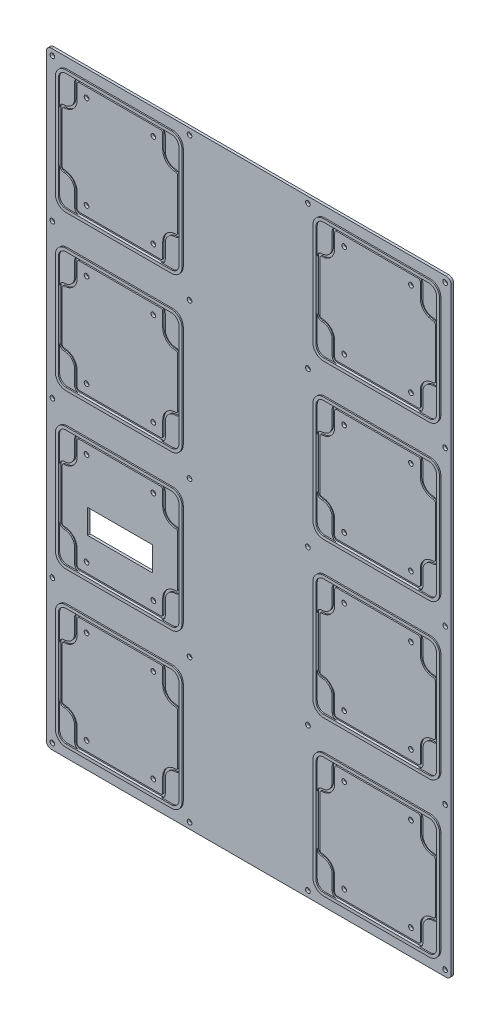
SolidWorks part; units mm, degrees
ref_plane "Front Plane" through (0, 0, 0) normal (0, 0, 1) x (1, 0, 0)
ref_plane "Top Plane" through (0, 0, 0) normal (0, 1, 0) x (1, 0, 0)
ref_plane "Right Plane" through (0, 0, 0) normal (1, 0, 0) x (0, 0, -1)
sketch "Sketch1" plane through (0, 0, 0) normal (0, 0, 1) x (1, 0, 0)
  line L1 (0, 0) -> (254, 0)
  line L2 (0, 0) -> (0, 381)
  line L3 (0, 381) -> (254, 381)
  line L4 (254, 0) -> (254, 381)
  dimension "D1" = 381
  dimension "D2" = 254
extrude "Boss-Extrude1" add sketch "Sketch1" along normal blind 1.5875
sketch "Sketch2" plane through (0, 0, 1.5875) normal (0, 0, 1) x (1, 0, 0)
  line L0 (89.8652, 377.19) -> (89.8652, 3.81) construction
  line L1 (0, 381) -> (254, 381) construction
  line L2 (127, 381) -> (127, 377.19) construction
  line L3 (3.81, 377.19) -> (250.19, 377.19) construction
  line L5 (164.1348, 377.19) -> (164.1348, 3.81) construction
  line L6 (3.81, 377.19) -> (3.81, 3.81) construction
  line L7 (3.81, 3.81) -> (250.19, 3.81) construction
  line L8 (250.19, 3.81) -> (250.19, 377.19) construction
  line L9 (3.81, 190.5) -> (250.19, 190.5) construction
  line L10 (3.81, 287.3756) -> (250.19, 287.3756) construction
  line L11 (3.81, 93.6244) -> (250.19, 93.6244) construction
  line L12 (0, 381) -> (0, 0) construction
  line L13 (0, 190.5) -> (3.81, 190.5) construction
  circle A0 centre (3.81, 377.19) radius 1.4732
  circle A1 centre (89.8652, 377.19) radius 1.4732
  circle A2 centre (164.1348, 377.19) radius 1.4732
  circle A3 centre (250.19, 377.19) radius 1.4732
  circle A4 centre (164.1348, 287.3755) radius 1.4732
  circle A5 centre (3.81, 287.3756) radius 1.4732
  circle A6 centre (250.19, 287.3756) radius 1.4732
  circle A7 centre (89.8652, 287.3756) radius 1.4732
  circle A8 centre (164.1348, 190.5) radius 1.4732
  circle A9 centre (3.81, 191.135) radius 1.4732
  circle A10 centre (250.19, 190.5) radius 1.4732
  circle A11 centre (89.8652, 190.5) radius 1.4732
  circle A12 centre (164.1348, 93.6244) radius 1.4732
  circle A13 centre (3.81, 93.6244) radius 1.4732
  circle A14 centre (250.19, 93.6244) radius 1.4732
  circle A15 centre (89.8652, 93.6244) radius 1.4732
  circle A16 centre (164.1348, 3.81) radius 1.4732
  circle A17 centre (3.81, 3.81) radius 1.4732
  circle A18 centre (250.19, 3.81) radius 1.4732
  circle A19 centre (89.8652, 3.81) radius 1.4732
  dimension "D6" = 2.9464
  dimension "D23" = 0
  dimension "D24" = 0
  dimension "D25" = 0
  dimension "D28" = 0
  dimension "D29" = 0
  dimension "D30" = 0
  dimension "D31" = 0
  dimension "D32" = 86.0552
  dimension "D1" = 246.38
  dimension "D3" = 373.38
  dimension "D4" = 96.8756
  dimension "D5" = 96.8756
  dimension "D7" = 86.0552
  dimension "D8" = 86.0552
  dimension "D9" = 0
  dimension "D10" = 0
  dimension "D11" = 0
  dimension "D12" = 86.0552
  dimension "D13" = 0
  dimension "D14" = 0
  dimension "D15" = 0
  dimension "D16" = 0
  dimension "D17" = 0
  dimension "D18" = 0
  dimension "D19" = 0
  dimension "D20" = 0
  dimension "D21" = 0
  dimension "D22" = 0
  dimension "D26" = 0
  dimension "D27" = 0
extrude "Cut-Extrude1" cut sketch "Sketch2" against normal through all contours A0 | A2 | A3
fillet "Fillet1" radius 3.175 4 edges at (254, 0, 0.7937) (0, 0, 0.7937) (254, 381, 0.7937) (0, 381, 0.7937)
sketch "Sketch3" plane through (0, 0, 1.5875) normal (0, 0, 1) x (1, 0, 0)
  line L0 (9.9695, 45.1866) -> (46.2026, 45.1866) construction
  line L1 (46.2026, 45.1866) -> (46.2026, 9.9695) construction
  line L2 (81.2038, 28.3591) -> (82.4357, 28.3591) construction
  line L3 (82.4357, 29.591) -> (82.4357, 60.7822)
  line L4 (73.0377, 11.2014) -> (73.0377, 20.193)
  line L5 (81.2038, 62.0141) -> (82.4357, 62.0141) construction
  line L6 (71.8058, 9.9695) -> (20.5994, 9.9695)
  line L7 (19.3675, 11.2014) -> (19.3675, 20.193)
  line L8 (11.2014, 28.3591) -> (9.9695, 28.3591) construction
  line L9 (9.9695, 29.591) -> (9.9695, 60.7822)
  line L10 (73.0377, 79.1718) -> (73.0377, 70.1802)
  line L11 (71.8058, 80.4037) -> (20.5994, 80.4037)
  line L12 (3.175, 0) -> (250.825, 0) construction
  line L13 (0, 377.825) -> (0, 3.175) construction
  line L14 (11.2014, 62.0141) -> (9.9695, 62.0141) construction
  line L15 (19.3675, 79.1718) -> (19.3675, 70.1802)
  line L16 (17.78, 79.1718) -> (17.78, 70.1802)
  line L17 (8.382, 29.591) -> (8.382, 60.7822)
  line L18 (17.78, 11.2014) -> (17.78, 20.193)
  line L19 (71.8058, 8.382) -> (20.5994, 8.382)
  line L20 (74.6252, 11.2014) -> (74.6252, 20.193)
  line L21 (84.0232, 29.591) -> (84.0232, 60.7822)
  line L22 (74.6252, 79.1718) -> (74.6252, 70.1802)
  line L23 (71.8058, 81.9912) -> (20.5994, 81.9912)
  arc A0 (19.3675, 20.193) -> (11.2014, 28.3591) centre (11.2014, 20.193) ccw
  arc A1 (9.9695, 29.591) -> (11.2014, 28.3591) centre (11.2014, 29.591) ccw
  arc A2 (19.3675, 11.2014) -> (20.5994, 9.9695) centre (20.5994, 11.2014) ccw
  arc A3 (73.0377, 11.2014) -> (71.8058, 9.9695) centre (71.8058, 11.2014) cw
  arc A4 (82.4357, 29.591) -> (81.2038, 28.3591) centre (81.2038, 29.591) cw
  arc A5 (73.0377, 20.193) -> (81.2038, 28.3591) centre (81.2038, 20.193) cw
  arc A6 (73.0377, 70.1802) -> (81.2038, 62.0141) centre (81.2038, 70.1802) ccw
  arc A7 (82.4357, 60.7822) -> (81.2038, 62.0141) centre (81.2038, 60.7822) ccw
  arc A8 (73.0377, 79.1718) -> (71.8058, 80.4037) centre (71.8058, 79.1718) ccw
  arc A9 (19.3675, 79.1718) -> (20.5994, 80.4037) centre (20.5994, 79.1718) cw
  arc A10 (9.9695, 60.7822) -> (11.2014, 62.0141) centre (11.2014, 60.7822) cw
  arc A11 (19.3675, 70.1802) -> (11.2014, 62.0141) centre (11.2014, 70.1802) cw
  arc A12 (17.78, 70.1802) -> (11.2014, 63.6016) centre (11.2014, 70.1802) cw
  arc A13 (8.382, 60.7822) -> (11.2014, 63.6016) centre (11.2014, 60.7822) cw
  arc A14 (8.382, 29.591) -> (11.2014, 26.7716) centre (11.2014, 29.591) ccw
  arc A15 (17.78, 20.193) -> (11.2014, 26.7716) centre (11.2014, 20.193) ccw
  arc A16 (17.78, 11.2014) -> (20.5994, 8.382) centre (20.5994, 11.2014) ccw
  arc A17 (74.6252, 11.2014) -> (71.8058, 8.382) centre (71.8058, 11.2014) cw
  arc A18 (74.6252, 20.193) -> (81.2038, 26.7716) centre (81.2038, 20.193) cw
  arc A19 (84.0232, 29.591) -> (81.2038, 26.7716) centre (81.2038, 29.591) cw
  arc A20 (84.0232, 60.7822) -> (81.2038, 63.6016) centre (81.2038, 60.7822) ccw
  arc A21 (74.6252, 70.1802) -> (81.2038, 63.6016) centre (81.2038, 70.1802) ccw
  arc A22 (74.6252, 79.1718) -> (71.8058, 81.9912) centre (71.8058, 79.1718) ccw
  arc A23 (17.78, 79.1718) -> (20.5994, 81.9912) centre (20.5994, 79.1718) cw
  point P35 (82.4357, 45.1866)
  dimension "D6" = 8.1661
  dimension "D7" = 2.4638
  dimension "D8" = 1.2319
  dimension "D1" = 9.9695
  dimension "D2" = 9.9695
  dimension "D3" = 19.3675
  dimension "D4" = 28.3591
  dimension "D5" = 45.1866
  dimension "D10" = 46.2026
  dimension "D9" = 1.5875
extrude "Cut-Extrude2" cut sketch "Sketch3" against normal blind 0.7937
sketch "Sketch4" plane through (0, 0, 1.5875) normal (0, 0, 1) x (1, 0, 0)
  line L0 (8.382, 60.7822) -> (8.382, 77.2287)
  line L1 (13.1445, 81.9912) -> (20.5994, 81.9912)
  line L2 (20.5994, 81.9912) -> (79.2607, 81.9912)
  line L3 (84.0232, 77.2287) -> (84.0232, 13.1445)
  line L4 (79.2607, 8.382) -> (13.1445, 8.382)
  line L5 (8.382, 13.1445) -> (8.382, 60.7822)
  line L6 (6.477, 60.7822) -> (6.477, 77.2287)
  line L7 (13.1445, 83.8962) -> (20.5994, 83.8962)
  line L8 (20.5994, 83.8962) -> (79.2607, 83.8962)
  line L9 (85.9282, 77.2287) -> (85.9282, 13.1445)
  line L10 (79.2607, 6.477) -> (13.1445, 6.477)
  line L11 (6.477, 13.1445) -> (6.477, 60.7822)
  arc A0 (13.1445, 81.9912) -> (8.382, 77.2287) centre (13.1445, 77.2287) ccw
  arc A1 (79.2607, 81.9912) -> (84.0232, 77.2287) centre (79.2607, 77.2287) cw
  arc A2 (84.0232, 13.1445) -> (79.2607, 8.382) centre (79.2607, 13.1445) cw
  arc A3 (8.382, 13.1445) -> (13.1445, 8.382) centre (13.1445, 13.1445) ccw
  arc A4 (13.1445, 83.8962) -> (6.477, 77.2287) centre (13.1445, 77.2287) ccw
  arc A5 (79.2607, 83.8962) -> (85.9282, 77.2287) centre (79.2607, 77.2287) cw
  arc A6 (85.9282, 13.1445) -> (79.2607, 6.477) centre (79.2607, 13.1445) cw
  arc A7 (6.477, 13.1445) -> (13.1445, 6.477) centre (13.1445, 13.1445) ccw
  dimension "D1" = 4.7625
  dimension "D2" = 1.905
extrude "Boss-Extrude2" add sketch "Sketch4" along normal blind 0.7937
sketch "Sketch5" plane through (0, 0, 1.5875) normal (0, 0, 1) x (1, 0, 0)
  line L0 (9.9695, 45.1866) -> (82.4357, 45.1866) construction
  line L1 (9.9695, 60.7822) -> (9.9695, 29.591) construction
  line L2 (82.4357, 29.591) -> (82.4357, 60.7822) construction
  line L3 (82.4357, 45.1866) -> (46.2026, 45.1866) construction
  line L4 (46.2026, 45.1866) -> (46.2026, 80.4037) construction
  line L5 (71.8058, 80.4037) -> (20.5994, 80.4037) construction
  circle A0 centre (25.2476, 74.3966) radius 1.4732
  circle A1 centre (67.1576, 74.3966) radius 1.4732
  circle A2 centre (67.1576, 15.9766) radius 1.4732
  circle A3 centre (25.2476, 15.9766) radius 1.4732
  dimension "D1" = 2.9464
  dimension "D2" = 20.955
  dimension "D3" = 29.21
extrude "Cut-Extrude3" cut sketch "Sketch5" against normal through all
pattern_linear "LPattern1" count 4 spacing 96.8756 along (0, 1, 0) count 2 spacing 161.5948 along (1, 0, 0) of "Cut-Extrude2", "Boss-Extrude2", "Cut-Extrude3"
sketch "Sketch6" plane through (0, 0, 1.5875) normal (0, 0, 1) x (1, 0, 0)
  line L0 (25.8826, 135.255) -> (9.9695, 135.255) construction
  line L1 (25.8826, 142.875) -> (66.5226, 142.875)
  line L2 (25.8826, 142.875) -> (25.8826, 127.635)
  line L3 (25.8826, 127.635) -> (66.5226, 127.635)
  line L4 (66.5226, 142.875) -> (66.5226, 127.635)
  line L5 (9.9695, 157.6578) -> (9.9695, 126.4666) construction
  line L6 (66.5226, 135.255) -> (82.4357, 135.255) construction
  line L7 (82.4357, 126.4666) -> (82.4357, 157.6578) construction
  line L8 (250.825, 381) -> (3.175, 381) construction
  line L10 (46.2026, 127.635) -> (46.2026, 106.8451) construction
  line L11 (20.5994, 106.8451) -> (71.8058, 106.8451) construction
  dimension "D1" = 15.24
  dimension "D2" = 40.64
  dimension "D3" = 238.125
extrude "Cut-Extrude4" cut sketch "Sketch6" against normal through all
